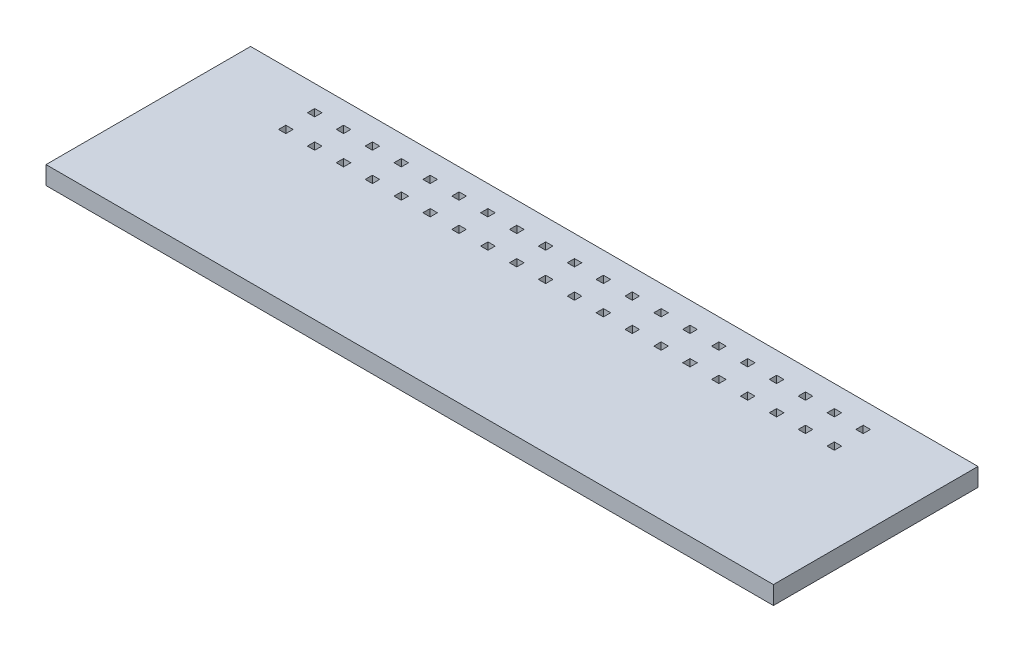
SolidWorks part; units mm, degrees
ref_plane "Front Plane" through (0, 0, 0) normal (0, 0, 1) x (1, 0, 0)
ref_plane "Top Plane" through (0, 0, 0) normal (0, 1, 0) x (1, 0, 0)
ref_plane "Right Plane" through (0, 0, 0) normal (1, 0, 0) x (0, 0, -1)
sketch "Sketch1" plane through (0, 0, 0) normal (0, 1, 0) x (1, 0, 0)
  line L1 (-32, -9) -> (32, -9)
  line L2 (-32, -9) -> (-32, 9)
  line L3 (-32, 9) -> (32, 9)
  line L4 (32, -9) -> (32, 9)
  line L5 (-32, -9) -> (32, 9) construction
  line L6 (-32, 9) -> (32, -9) construction
  point P0 (0, 0)
  dimension "D1" = 18
  dimension "D2" = 64
extrude "Boss-Extrude1" add sketch "Sketch1" along normal blind 1.6
sketch "Sketch2" plane through (0, 1.6, 0) normal (0, 1, 0) x (1, 0, 0)
  line L0 (0, -9) -> (0, 9) construction
  line L1 (-32, -9) -> (32, -9) construction
  line L2 (32, 9) -> (-32, 9) construction
  line L3 (-32, 0) -> (32, 0) construction
  line L4 (-32, 9) -> (-32, -9) construction
  line L5 (32, -9) -> (32, 9) construction
  line L6 (-25.65, 6.77) -> (25.65, 6.77) construction
  line L7 (-25.65, 3) -> (25.65, 3)
  line L8 (-25.65, 3) -> (-25.65, 8)
  line L9 (-25.65, 8) -> (25.65, 8)
  line L10 (25.65, 3) -> (25.65, 8)
  line L11 (-25.65, 3) -> (25.65, 8) construction
  line L12 (-25.65, 8) -> (25.65, 3) construction
  line L13 (-25.65, 5.5) -> (25.65, 5.5) construction
  line L14 (-25.65, 4.23) -> (25.65, 4.23) construction
  line L15 (-21.91, 6.45) -> (-21.91, 7.09)
  line L16 (-24.45, 6.45) -> (-23.81, 6.45)
  line L17 (-24.45, 6.45) -> (-24.45, 7.09)
  line L18 (-24.45, 7.09) -> (-23.81, 7.09)
  line L19 (-23.81, 6.45) -> (-23.81, 7.09)
  line L20 (-24.45, 6.45) -> (-23.81, 7.09) construction
  line L21 (-24.45, 7.09) -> (-23.81, 6.45) construction
  line L22 (-21.91, 6.45) -> (-21.27, 6.45)
  line L23 (-21.27, 6.45) -> (-21.27, 7.09)
  line L24 (-21.91, 7.09) -> (-21.27, 7.09)
  line L25 (-19.37, 6.45) -> (-19.37, 7.09)
  line L26 (-19.37, 6.45) -> (-18.73, 6.45)
  line L27 (-18.73, 6.45) -> (-18.73, 7.09)
  line L28 (-19.37, 7.09) -> (-18.73, 7.09)
  line L29 (-16.83, 6.45) -> (-16.83, 7.09)
  line L30 (-16.83, 6.45) -> (-16.19, 6.45)
  line L31 (-16.19, 6.45) -> (-16.19, 7.09)
  line L32 (-16.83, 7.09) -> (-16.19, 7.09)
  line L33 (-14.29, 6.45) -> (-14.29, 7.09)
  line L34 (-14.29, 6.45) -> (-13.65, 6.45)
  line L35 (-13.65, 6.45) -> (-13.65, 7.09)
  line L36 (-14.29, 7.09) -> (-13.65, 7.09)
  line L37 (-11.75, 6.45) -> (-11.75, 7.09)
  line L38 (-11.75, 6.45) -> (-11.11, 6.45)
  line L39 (-11.11, 6.45) -> (-11.11, 7.09)
  line L40 (-11.75, 7.09) -> (-11.11, 7.09)
  line L41 (-9.21, 6.45) -> (-9.21, 7.09)
  line L42 (-9.21, 6.45) -> (-8.57, 6.45)
  line L43 (-8.57, 6.45) -> (-8.57, 7.09)
  line L44 (-9.21, 7.09) -> (-8.57, 7.09)
  line L45 (-6.67, 6.45) -> (-6.67, 7.09)
  line L46 (-6.67, 6.45) -> (-6.03, 6.45)
  line L47 (-6.03, 6.45) -> (-6.03, 7.09)
  line L48 (-6.67, 7.09) -> (-6.03, 7.09)
  line L49 (-4.13, 6.45) -> (-4.13, 7.09)
  line L50 (-4.13, 6.45) -> (-3.49, 6.45)
  line L51 (-3.49, 6.45) -> (-3.49, 7.09)
  line L52 (-4.13, 7.09) -> (-3.49, 7.09)
  line L53 (-1.59, 6.45) -> (-1.59, 7.09)
  line L54 (-1.59, 6.45) -> (-0.95, 6.45)
  line L55 (-0.95, 6.45) -> (-0.95, 7.09)
  line L56 (-1.59, 7.09) -> (-0.95, 7.09)
  line L57 (24.45, 7.09) -> (23.81, 7.09)
  line L58 (23.81, 6.45) -> (23.81, 7.09)
  line L59 (24.45, 6.45) -> (23.81, 6.45)
  line L60 (24.45, 6.45) -> (24.45, 7.09)
  line L61 (21.91, 6.45) -> (21.27, 6.45)
  line L62 (21.27, 6.45) -> (21.27, 7.09)
  line L63 (21.91, 7.09) -> (21.27, 7.09)
  line L64 (21.91, 6.45) -> (21.91, 7.09)
  line L65 (19.37, 6.45) -> (18.73, 6.45)
  line L66 (18.73, 6.45) -> (18.73, 7.09)
  line L67 (19.37, 7.09) -> (18.73, 7.09)
  line L68 (19.37, 6.45) -> (19.37, 7.09)
  line L69 (16.83, 6.45) -> (16.19, 6.45)
  line L70 (16.19, 6.45) -> (16.19, 7.09)
  line L71 (16.83, 7.09) -> (16.19, 7.09)
  line L72 (16.83, 6.45) -> (16.83, 7.09)
  line L73 (14.29, 6.45) -> (13.65, 6.45)
  line L74 (13.65, 6.45) -> (13.65, 7.09)
  line L75 (14.29, 7.09) -> (13.65, 7.09)
  line L76 (14.29, 6.45) -> (14.29, 7.09)
  line L77 (11.75, 6.45) -> (11.11, 6.45)
  line L78 (11.11, 6.45) -> (11.11, 7.09)
  line L79 (11.75, 7.09) -> (11.11, 7.09)
  line L80 (11.75, 6.45) -> (11.75, 7.09)
  line L81 (9.21, 6.45) -> (8.57, 6.45)
  line L82 (8.57, 6.45) -> (8.57, 7.09)
  line L83 (9.21, 7.09) -> (8.57, 7.09)
  line L84 (9.21, 6.45) -> (9.21, 7.09)
  line L85 (6.67, 6.45) -> (6.03, 6.45)
  line L86 (6.03, 6.45) -> (6.03, 7.09)
  line L87 (6.67, 7.09) -> (6.03, 7.09)
  line L88 (6.67, 6.45) -> (6.67, 7.09)
  line L89 (4.13, 6.45) -> (3.49, 6.45)
  line L90 (3.49, 6.45) -> (3.49, 7.09)
  line L91 (4.13, 7.09) -> (3.49, 7.09)
  line L92 (4.13, 6.45) -> (4.13, 7.09)
  line L93 (1.59, 6.45) -> (0.95, 6.45)
  line L94 (0.95, 6.45) -> (0.95, 7.09)
  line L95 (1.59, 7.09) -> (0.95, 7.09)
  line L96 (1.59, 6.45) -> (1.59, 7.09)
  line L97 (-24.45, 3.91) -> (-23.81, 3.91)
  line L98 (-23.81, 4.55) -> (-23.81, 3.91)
  line L99 (-24.45, 4.55) -> (-23.81, 4.55)
  line L100 (-24.45, 4.55) -> (-24.45, 3.91)
  line L101 (-21.91, 4.55) -> (-21.27, 4.55)
  line L102 (-21.27, 4.55) -> (-21.27, 3.91)
  line L103 (-21.91, 3.91) -> (-21.27, 3.91)
  line L104 (-21.91, 4.55) -> (-21.91, 3.91)
  line L105 (-19.37, 4.55) -> (-18.73, 4.55)
  line L106 (-18.73, 4.55) -> (-18.73, 3.91)
  line L107 (-19.37, 3.91) -> (-18.73, 3.91)
  line L108 (-19.37, 4.55) -> (-19.37, 3.91)
  line L109 (-16.83, 4.55) -> (-16.19, 4.55)
  line L110 (-16.19, 4.55) -> (-16.19, 3.91)
  line L111 (-16.83, 3.91) -> (-16.19, 3.91)
  line L112 (-16.83, 4.55) -> (-16.83, 3.91)
  line L113 (-14.29, 4.55) -> (-13.65, 4.55)
  line L114 (-13.65, 4.55) -> (-13.65, 3.91)
  line L115 (-14.29, 3.91) -> (-13.65, 3.91)
  line L116 (-14.29, 4.55) -> (-14.29, 3.91)
  line L117 (-11.75, 4.55) -> (-11.11, 4.55)
  line L118 (-11.11, 4.55) -> (-11.11, 3.91)
  line L119 (-11.75, 3.91) -> (-11.11, 3.91)
  line L120 (-11.75, 4.55) -> (-11.75, 3.91)
  line L121 (-9.21, 4.55) -> (-8.57, 4.55)
  line L122 (-8.57, 4.55) -> (-8.57, 3.91)
  line L123 (-9.21, 3.91) -> (-8.57, 3.91)
  line L124 (-9.21, 4.55) -> (-9.21, 3.91)
  line L125 (-4.13, 4.55) -> (-3.49, 4.55)
  line L126 (-3.49, 4.55) -> (-3.49, 3.91)
  line L127 (-4.13, 3.91) -> (-3.49, 3.91)
  line L128 (-4.13, 4.55) -> (-4.13, 3.91)
  line L129 (-6.67, 4.55) -> (-6.03, 4.55)
  line L130 (-6.03, 4.55) -> (-6.03, 3.91)
  line L131 (-6.67, 3.91) -> (-6.03, 3.91)
  line L132 (-6.67, 4.55) -> (-6.67, 3.91)
  line L133 (6.67, 4.55) -> (6.67, 3.91)
  line L134 (6.67, 3.91) -> (6.03, 3.91)
  line L135 (6.03, 4.55) -> (6.03, 3.91)
  line L136 (6.67, 4.55) -> (6.03, 4.55)
  line L137 (9.21, 4.55) -> (9.21, 3.91)
  line L138 (9.21, 3.91) -> (8.57, 3.91)
  line L139 (8.57, 4.55) -> (8.57, 3.91)
  line L140 (9.21, 4.55) -> (8.57, 4.55)
  line L141 (11.75, 4.55) -> (11.75, 3.91)
  line L142 (11.75, 3.91) -> (11.11, 3.91)
  line L143 (11.11, 4.55) -> (11.11, 3.91)
  line L144 (11.75, 4.55) -> (11.11, 4.55)
  line L145 (14.29, 4.55) -> (14.29, 3.91)
  line L146 (14.29, 3.91) -> (13.65, 3.91)
  line L147 (13.65, 4.55) -> (13.65, 3.91)
  line L148 (14.29, 4.55) -> (13.65, 4.55)
  line L149 (16.83, 4.55) -> (16.83, 3.91)
  line L150 (16.83, 3.91) -> (16.19, 3.91)
  line L151 (16.19, 4.55) -> (16.19, 3.91)
  line L152 (16.83, 4.55) -> (16.19, 4.55)
  line L153 (19.37, 4.55) -> (19.37, 3.91)
  line L154 (19.37, 3.91) -> (18.73, 3.91)
  line L155 (18.73, 4.55) -> (18.73, 3.91)
  line L156 (19.37, 4.55) -> (18.73, 4.55)
  line L157 (21.91, 4.55) -> (21.91, 3.91)
  line L158 (21.91, 3.91) -> (21.27, 3.91)
  line L159 (21.27, 4.55) -> (21.27, 3.91)
  line L160 (21.91, 4.55) -> (21.27, 4.55)
  line L161 (24.45, 4.55) -> (24.45, 3.91)
  line L162 (24.45, 4.55) -> (23.81, 4.55)
  line L163 (23.81, 4.55) -> (23.81, 3.91)
  line L164 (24.45, 3.91) -> (23.81, 3.91)
  line L165 (4.13, 4.55) -> (4.13, 3.91)
  line L166 (4.13, 3.91) -> (3.49, 3.91)
  line L167 (3.49, 4.55) -> (3.49, 3.91)
  line L168 (4.13, 4.55) -> (3.49, 4.55)
  line L169 (1.59, 4.55) -> (1.59, 3.91)
  line L170 (1.59, 3.91) -> (0.95, 3.91)
  line L171 (0.95, 4.55) -> (0.95, 3.91)
  line L172 (1.59, 4.55) -> (0.95, 4.55)
  line L173 (-1.59, 4.55) -> (-0.95, 4.55)
  line L174 (-0.95, 4.55) -> (-0.95, 3.91)
  line L175 (-1.59, 3.91) -> (-0.95, 3.91)
  line L176 (-1.59, 4.55) -> (-1.59, 3.91)
  point P12 (0, 5.5)
  point P23 (-24.13, 6.77)
  point P29 (-24.13, 7.09)
  point P65 (-21.59, 7.09)
  point P106 (-1.27, 7.09)
  point P107 (1.27, 7.09)
  dimension "D1" = 5
  dimension "D2" = 51.3
  dimension "D3" = 3.5
  dimension "D4" = 2.54
  dimension "D5" = 0.64
  dimension "D6" = 10
  dimension "D7" = 2.54
  dimension "D8" = 2.54
extrude "Cut-Extrude2" cut sketch "Sketch2" against normal through all contours L24 L15 L22 L23 | L19 L18 L17 L16 | L98 L97 L100 L99 | L102 L103 L104 L101 | L27 L28 L25 L26 | L106 L107 L108 L105 | L110 L111 L112 L109 | L30 L31 L32 L29 | L34 L35 L36 L33 | L113 L114 L115 L116 | L37 L40 L39 L38 | L117 L118 L119 L120 | L44 L43 L42 L41 | L121 L122 L123 L124 | L129 L130 L131 L132 | L48 L47 L46 L45 | L52 L51 L50 L49 | L125 L126 L127 L128 | L173 L174 L175 L176 | L172 L171 L170 L169 | L55 L56 L53 L54 | L94 L95 L96 L93 | L90 L91 L92 L89 | L168 L167 L166 L165 | L136 L135 L134 L133 | L140 L139 L138 L137 | L88 L87 L86 L85 | L84 L83 L82 L81 | L78 L79 L80 L77 | L142 L143 L144 L141 | L73 L74 L75 L76 | L148 L147 L146 L145 | L69 L70 L71 L72 | L152 L151 L150 L149 | L65 L66 L67 L68 | L156 L155 L154 L153 | L61 L62 L63 L64 | L160 L159 L158 L157 | L162 L163 L164 L161 | L59 L58 L57 L60
